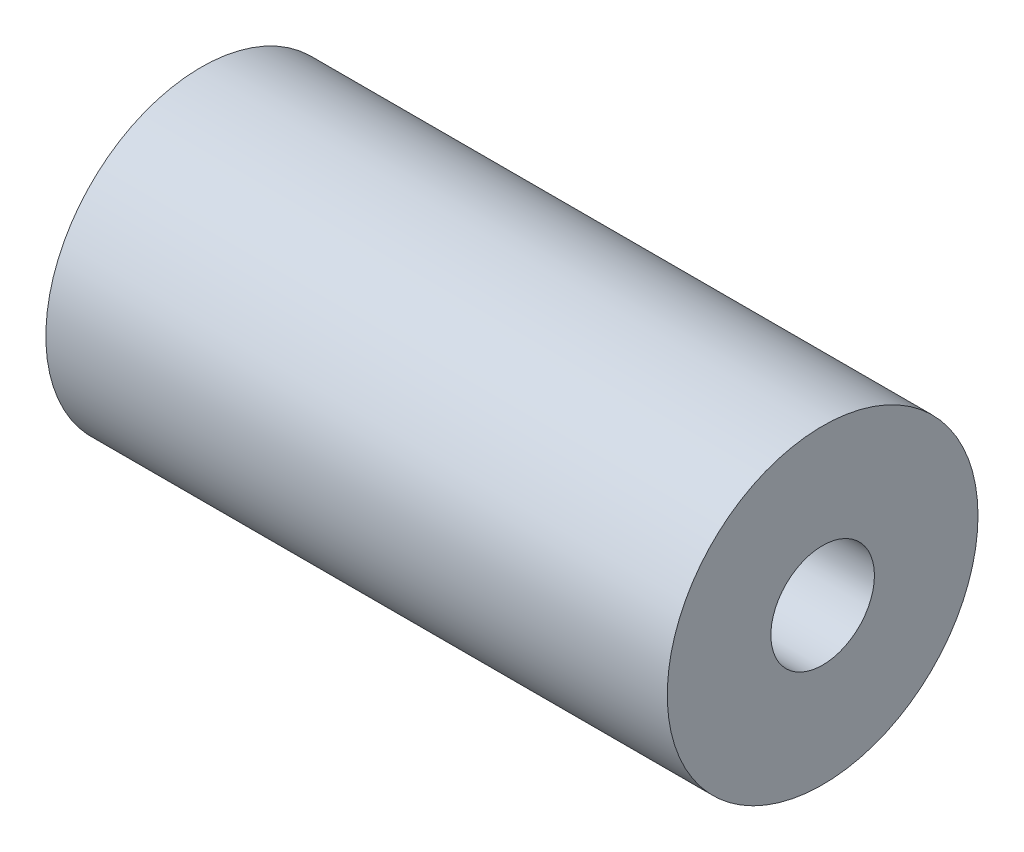
SolidWorks part; units mm, degrees
material "Polyurethane Foam Flexible"
ref_plane "Front Plane" through (0, 0, 0) normal (0, 0, 1) x (1, 0, 0)
ref_plane "Top Plane" through (0, 0, 0) normal (0, 1, 0) x (1, 0, 0)
ref_plane "Right Plane" through (0, 0, 0) normal (1, 0, 0) x (0, 0, -1)
sketch "Sketch1" plane through (0, 0, 0) normal (1, 0, 0) x (0, 0, -1)
  circle A0 centre (0, 0) radius 30
  circle A1 centre (0, 0) radius 10
  dimension "D1" = 60
  dimension "D2" = 20
extrude "Boss-Extrude1" add sketch "Sketch1" along normal blind 120
